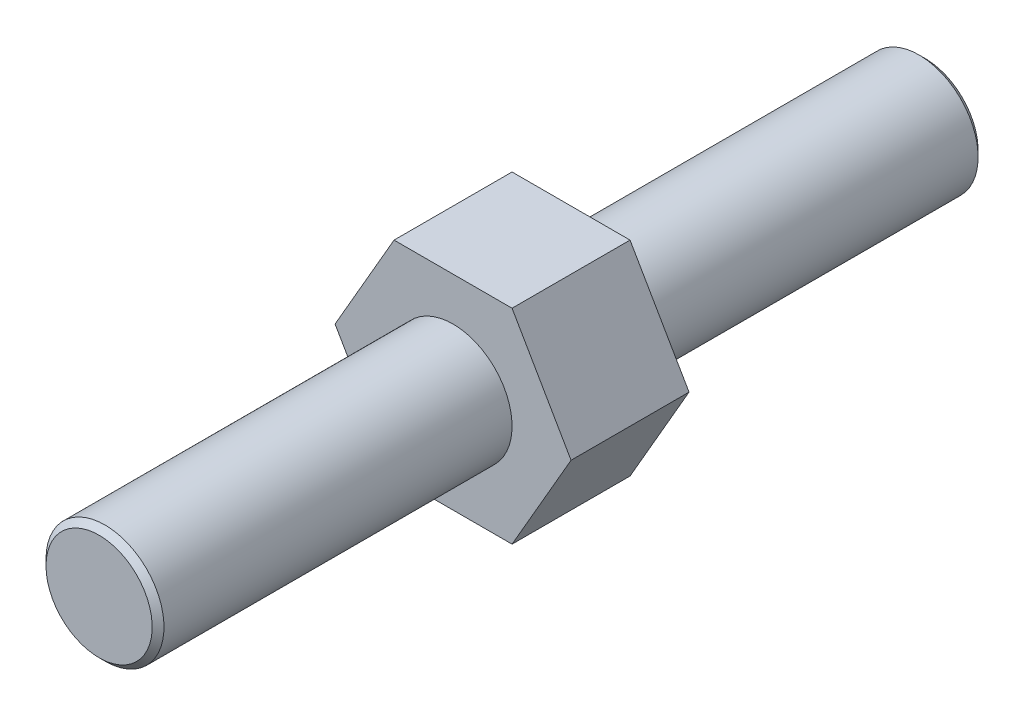
SolidWorks part; units mm, degrees
ref_plane "Plan de face" through (0, 0, 0) normal (0, 0, 1) x (1, 0, 0)
ref_plane "Plan de dessus" through (0, 0, 0) normal (0, 1, 0) x (1, 0, 0)
ref_plane "Plan de droite" through (0, 0, 0) normal (1, 0, 0) x (0, 0, -1)
sketch "Esquisse1" plane through (0, 0, 0) normal (0, 0, 1) x (1, 0, 0)
  line L0 (-10, 17.3205) -> (10, 17.3205)
  line L1 (10, 17.3205) -> (20, 0)
  line L4 (20, 0) -> (10, -17.3205)
  line L5 (10, -17.3205) -> (-10, -17.3205)
  line L6 (-10, -17.3205) -> (-20, 0)
  line L7 (-10, 17.3205) -> (-20, 0)
  line L10 (-20, 0) -> (20, 0) construction
  line L12 (-10, -17.3205) -> (10, 17.3205) construction
  line L14 (10, -17.3205) -> (-10, 17.3205) construction
  point P2 (0, 0)
  dimension "D1" = 60
  dimension "D2" = 60
  dimension "D3" = 20
  dimension "D4" = 20
  dimension "D5" = 20
extrude "Boss.-Extru.1" add sketch "Esquisse1" along normal blind 10 contours L1 L4 L5 L6 L7 L0
sketch "Esquisse2" plane through (0, 0, 0) normal (0, 1, 0) x (1, 0, 0)
  line L0 (0, -10) -> (0, -70)
  line L1 (-10, -10) -> (10, -10) construction
  line L2 (0, -70) -> (9, -70)
  line L3 (9, -70) -> (10, -69)
  line L4 (10, -69) -> (10, -10)
  line L5 (0, -10) -> (10, -10)
  dimension "D1" = 10
  dimension "D2" = 1
  dimension "D3" = 1
  dimension "D4" = 60
revolve "Révolution1" add sketch "Esquisse2" angle 360 about L0
mirror "Symétrie1" about plane through (0, 0, 0) normal (0, 0, -1) of "Boss.-Extru.1", "Révolution1"
